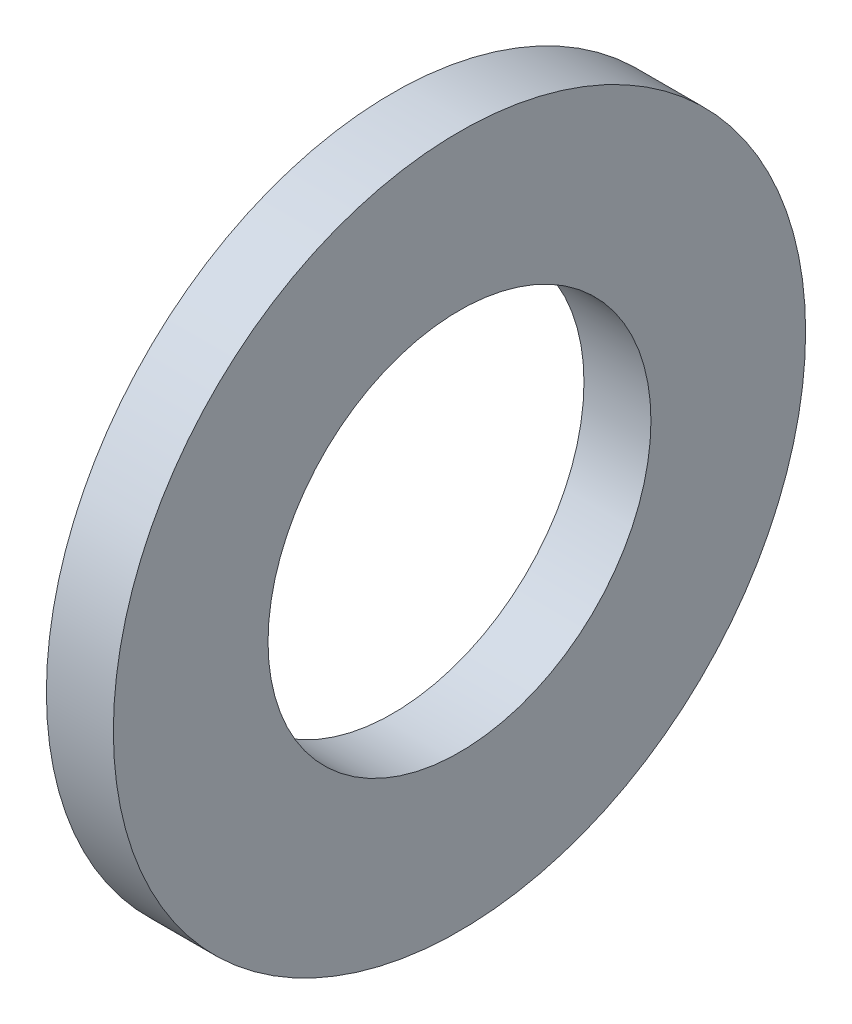
SolidWorks part; units mm, degrees
material "AISI 304"
ref_plane "Front Plane" through (0, 0, 0) normal (0, 0, 1) x (1, 0, 0)
ref_plane "Top Plane" through (0, 0, 0) normal (0, 1, 0) x (1, 0, 0)
ref_plane "Right Plane" through (0, 0, 0) normal (1, 0, 0) x (0, 0, -1)
sketch "Sketch1" plane through (0, 0, 0) normal (1, 0, 0) x (0, 0, -1)
  circle A0 centre (0, 0) radius 9.3218
  circle A1 centre (0, 0) radius 5.1562
  dimension "OD" = 18.6436
  dimension "ID" = 10.3124
extrude "Boss-Extrude1" add sketch "Sketch1" along normal blind 1.8034
